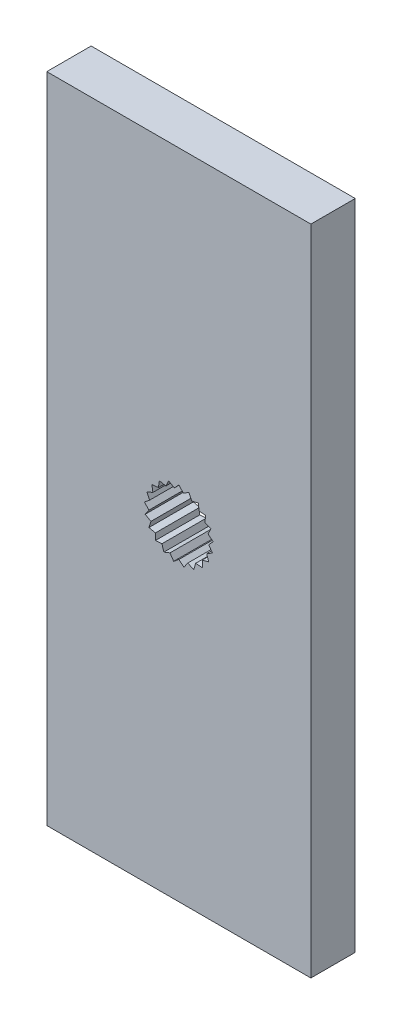
SolidWorks part; units mm, degrees
ref_plane "Front Plane" through (0, 0, 0) normal (0, 0, 1) x (1, 0, 0)
ref_plane "Top Plane" through (0, 0, 0) normal (0, 1, 0) x (1, 0, 0)
ref_plane "Right Plane" through (0, 0, 0) normal (1, 0, 0) x (0, 0, -1)
sketch "Model" plane through (0, 0, 0) normal (0, 0, 1) x (1, 0, 0)
  line L160 (-478.3454, 210.503) -> (-478.0431, 210.1768)
  line L161 (-478.0431, 210.1768) -> (-477.6584, 210.3991)
  line L162 (-477.6584, 210.3991) -> (-477.4655, 209.9981)
  line L163 (-477.4655, 209.9981) -> (-477.0325, 210.0969)
  line L164 (-477.0325, 210.0969) -> (-476.9659, 209.6567)
  line L165 (-476.9659, 209.6567) -> (-476.5232, 209.623)
  line L166 (-476.5232, 209.623) -> (-476.589, 209.1827)
  line L167 (-476.589, 209.1827) -> (-476.1758, 209.0197)
  line L168 (-476.1758, 209.0197) -> (-476.3682, 208.6184)
  line L169 (-476.3682, 208.6184) -> (-476.0213, 208.3405)
  line L170 (-476.0213, 208.3405) -> (-476.323, 208.0138)
  line L171 (-476.323, 208.0138) -> (-476.0732, 207.6458)
  line L172 (-476.0732, 207.6458) -> (-476.4575, 207.4228)
  line L173 (-476.4575, 207.4228) -> (-476.327, 206.9973)
  line L174 (-476.327, 206.9973) -> (-476.7598, 206.8979)
  line L175 (-476.7598, 206.8979) -> (-476.7601, 206.4526)
  line L176 (-476.7601, 206.4526) -> (-477.2029, 206.4855)
  line L177 (-477.2029, 206.4855) -> (-477.3341, 206.0602)
  line L178 (-477.3341, 206.0602) -> (-477.7476, 206.2225)
  line L179 (-477.7476, 206.2225) -> (-477.998, 205.8548)
  line L180 (-477.998, 205.8548) -> (-478.3454, 206.1321)
  line L181 (-478.3454, 206.1321) -> (-478.6928, 205.8548)
  line L182 (-478.6928, 205.8548) -> (-478.9432, 206.2225)
  line L183 (-478.9432, 206.2225) -> (-479.3567, 206.0602)
  line L184 (-479.3567, 206.0602) -> (-479.4879, 206.4855)
  line L185 (-479.4879, 206.4855) -> (-479.9307, 206.4526)
  line L186 (-479.9307, 206.4526) -> (-479.931, 206.8979)
  line L187 (-479.931, 206.8979) -> (-480.3638, 206.9973)
  line L188 (-480.3638, 206.9973) -> (-480.2333, 207.4228)
  line L189 (-480.2333, 207.4228) -> (-480.6176, 207.6458)
  line L190 (-480.6176, 207.6458) -> (-480.3678, 208.0138)
  line L191 (-480.3678, 208.0138) -> (-480.6695, 208.3405)
  line L192 (-480.6695, 208.3405) -> (-480.3226, 208.6184)
  line L193 (-480.3226, 208.6184) -> (-480.515, 209.0197)
  line L194 (-480.515, 209.0197) -> (-480.1018, 209.1827)
  line L195 (-480.1018, 209.1827) -> (-480.1676, 209.623)
  line L196 (-480.1676, 209.623) -> (-479.7249, 209.6567)
  line L197 (-479.7249, 209.6567) -> (-479.6583, 210.0969)
  line L198 (-479.6583, 210.0969) -> (-479.2253, 209.9981)
  line L199 (-479.2253, 209.9981) -> (-479.0324, 210.3991)
  line L200 (-479.0324, 210.3991) -> (-478.6477, 210.1768)
  line L201 (-478.6477, 210.1768) -> (-478.3454, 210.503)
  line L202 (-487.275, 186.0896) -> (-487.275, 230.2419)
  line L203 (-487.275, 230.2419) -> (-469.4158, 230.2419)
  line L204 (-469.4158, 230.2419) -> (-469.4158, 186.0896)
  line L205 (-469.4158, 186.0896) -> (-487.275, 186.0896)
extrude "Boss-Extrude1" add sketch "Model" along normal blind 3
sketch "Sketch1" plane through (0, 0, 3) normal (0, 0, 1) x (1, 0, 0)
  line L0 (-469.4158, 208.1657) -> (-487.275, 208.1657) construction
  line L1 (-469.4158, 186.0896) -> (-469.4158, 230.2419) construction
  line L2 (-487.275, 230.2419) -> (-487.275, 186.0896) construction
  line L3 (-478.3454, 230.2419) -> (-478.3454, 186.0896) construction
  line L4 (-469.4158, 230.2419) -> (-487.275, 230.2419) construction
  line L5 (-487.275, 186.0896) -> (-469.4158, 186.0896) construction
  circle A0 centre (-478.3454, 208.1657) radius 2.3341
